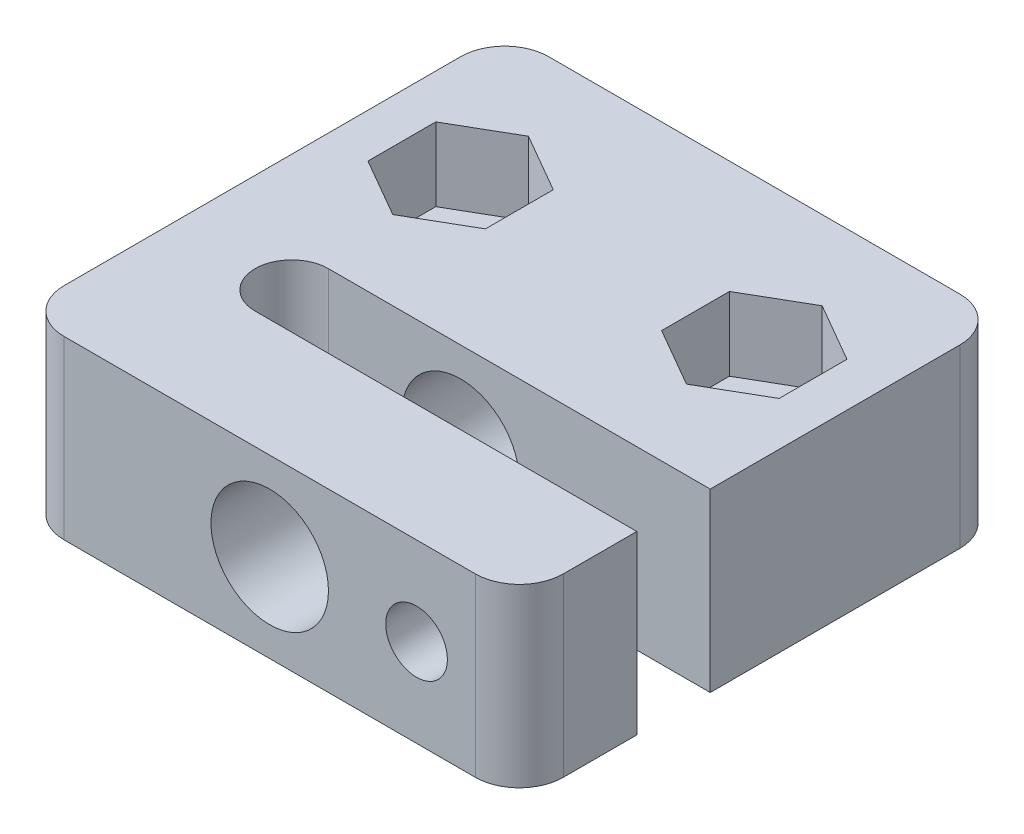
SolidWorks part; units mm, degrees
material "POM Acetal Copolymer"
ref_plane "Front Plane" through (0, 0, 0) normal (0, 0, 1) x (1, 0, 0)
ref_plane "Top Plane" through (0, 0, 0) normal (0, 1, 0) x (1, 0, 0)
ref_plane "Right Plane" through (0, 0, 0) normal (1, 0, 0) x (0, 0, -1)
sketch "Sketch1" plane through (0, 0, 0) normal (0, 1, 0) x (1, 0, 0)
  line L1 (-17, 16.5) -> (17, 16.5)
  line L2 (-17, 16.5) -> (-17, -16.5)
  line L3 (-17, -16.5) -> (17, -16.5)
  line L4 (17, 16.5) -> (17, -16.5)
  line L5 (-17, 16.5) -> (17, -16.5) construction
  line L6 (-17, -16.5) -> (17, 16.5) construction
  point P0 (0, 0)
  dimension "D1" = 34
  dimension "D2" = 33
extrude "Boss-Extrude1" add sketch "Sketch1" along normal blind 12
sketch "Sketch2" plane through (0, 0, 0) normal (0, -1, 0) x (1, 0, 0)
  line L6 (17, 16.5) -> (17, -16.5) construction
  line L7 (17, 8.5) -> (-9, 8.5)
  line L8 (17, 8.5) -> (17, 3.5)
  line L9 (17, 3.5) -> (-9, 3.5)
  line L11 (-17, 16.5) -> (17, 16.5) construction
  arc A1 (-9, 8.5) -> (-9, 3.5) centre (-9, 6) ccw
  dimension "D1" = 8
  dimension "D2" = 5
  dimension "D3" = 26
extrude "Cut-Extrude1" cut sketch "Sketch2" against normal through all
sketch "Sketch3" plane through (0, 12, 0) normal (0, 1, 0) x (1, 0, 0)
  line L0 (-17, 16.5) -> (-17, -16.5) construction
  line L1 (-10, 1.88) -> (-5.999, 4.19)
  line L2 (-5.999, 4.19) -> (-5.999, 8.81)
  line L3 (-5.999, 8.81) -> (-10, 11.12)
  line L4 (-10, 11.12) -> (-14.001, 8.81)
  line L5 (-14.001, 8.81) -> (-14.001, 4.19)
  line L6 (-14.001, 4.19) -> (-10, 1.88)
  line L7 (17, 16.5) -> (-17, 16.5) construction
  line L8 (0, 16.5) -> (0, -16.5) construction
  line L9 (-17, -16.5) -> (17, -16.5) construction
  line L10 (14.001, 4.19) -> (10, 1.88)
  line L11 (14.001, 8.81) -> (14.001, 4.19)
  line L12 (10, 11.12) -> (14.001, 8.81)
  line L13 (5.999, 8.81) -> (10, 11.12)
  line L14 (5.999, 4.19) -> (5.999, 8.81)
  line L15 (10, 1.88) -> (5.999, 4.19)
  circle A0 centre (-10, 6.5) radius 4.001 construction
  circle A1 centre (10, 6.5) radius 4.001 construction
  dimension "D1" = 7
  dimension "D2" = 10
  dimension "D3" = 4.62
extrude "Cut-Extrude2" cut sketch "Sketch3" against normal blind 5
hole_wizard "Ø8.0 (8) Diameter Hole1" positions "Sketch6" profile "Sketch7" hole size "Ø8.0" standard "ANSI Metric" end condition through all
sketch "Sketch6" plane through (0, 0, 16.5) normal (0, 0, 1) x (1, 0, 0)
  point P0 (0, 6)
sketch "Sketch7" plane through (0, 6, 16.5) normal (1, 0, 0) x (0, -1, 0)
  line L0 (0, 0) -> (0, 33)
  line L1 (0, 33) -> (4, 33)
  line L2 (4, 33) -> (4, 0)
  line L5 (4, 0) -> (0, 0)
  line L11 (0, -6.35) -> (0, 107.95) construction
  dimension "Thru Hole Dia." = 8
  dimension "Thru Hole Depth" = 33
sketch "Sketch8" plane through (0, 0, 16.5) normal (0, 0, 1) x (1, 0, 0)
  line L0 (0, 6) -> (10, 6) construction
  dimension "D1" = 10
hole_wizard "Ø4.2 (4.2) Diameter Hole1" positions "Sketch9" profile "Sketch10" hole size "Ø4.2" standard "ANSI Metric"
sketch "Sketch9" plane through (0, 0, 16.5) normal (0, 0, 1) x (1, 0, 0)
  point P0 (10, 6)
sketch "Sketch10" plane through (10, 6, 16.5) normal (1, 0, 0) x (0, -1, 0)
  line L0 (0, 0) -> (0, 8)
  line L1 (0, 8) -> (2.1, 8)
  line L2 (2.1, 8) -> (2.1, 0)
  line L5 (2.1, 0) -> (0, 0)
  line L11 (0, -6.35) -> (0, 107.95) construction
  dimension "Thru Hole Dia." = 4.2
  dimension "Thru Hole Depth" = 8
sketch "Sketch11" plane through (0, 0, 0) normal (0, -1, 0) x (1, 0, 0)
  line L0 (-17, -6.5) -> (17, -6.5) construction
  line L1 (-17, -16.5) -> (-17, 16.5) construction
  line L2 (17, 3.5) -> (17, -16.5) construction
  line L3 (17, -16.5) -> (-17, -16.5) construction
  line L4 (-10, -16.5) -> (-10, -6.5) construction
  line L5 (10, -16.5) -> (10, -6.5) construction
  point P12 (-10, -6.5)
  point P13 (10, -6.5)
  dimension "D1" = 10
  dimension "D2" = 7
  dimension "D3" = 7
hole_wizard "Hole1" positions "3DSketch1" profile "Sketch12" legacy
sketch3d "3DSketch1"
  point P0 (-10, 0, -6.5)
  point P3 (10, 0, -6.5)
sketch "Sketch12" plane through (-10, 0, -6.5) normal (1, 0, 0) x (0, 0, -1)
  line L0 (0, 0) -> (0, 13.5322)
  line L1 (0, 13.5322) -> (2.55, 12)
  line L2 (2.55, 12) -> (2.55, 2)
  line L3 (2.55, 2) -> (4.5, 2)
  line L4 (4.5, 0) -> (0, 0)
  line L5 (0, -11.3109) -> (0, 121.1557) construction
  line L6 (0, 13.5322) -> (-2.55, 12) construction
  line L7 (4.5, 2) -> (4.5, 0)
  dimension "Depth" = 12
  dimension "Drill Angle" = 118
  dimension "Diameter" = 5.1
  dimension "C-Bore Diameter" = 9
  dimension "C-Bore Depth" = 2
fillet "Fillet1" radius 3 4 edges at (17, 6, -16.5) (-17, 6, -16.5) (17, 6, 16.5) (-17, 6, 16.5)
